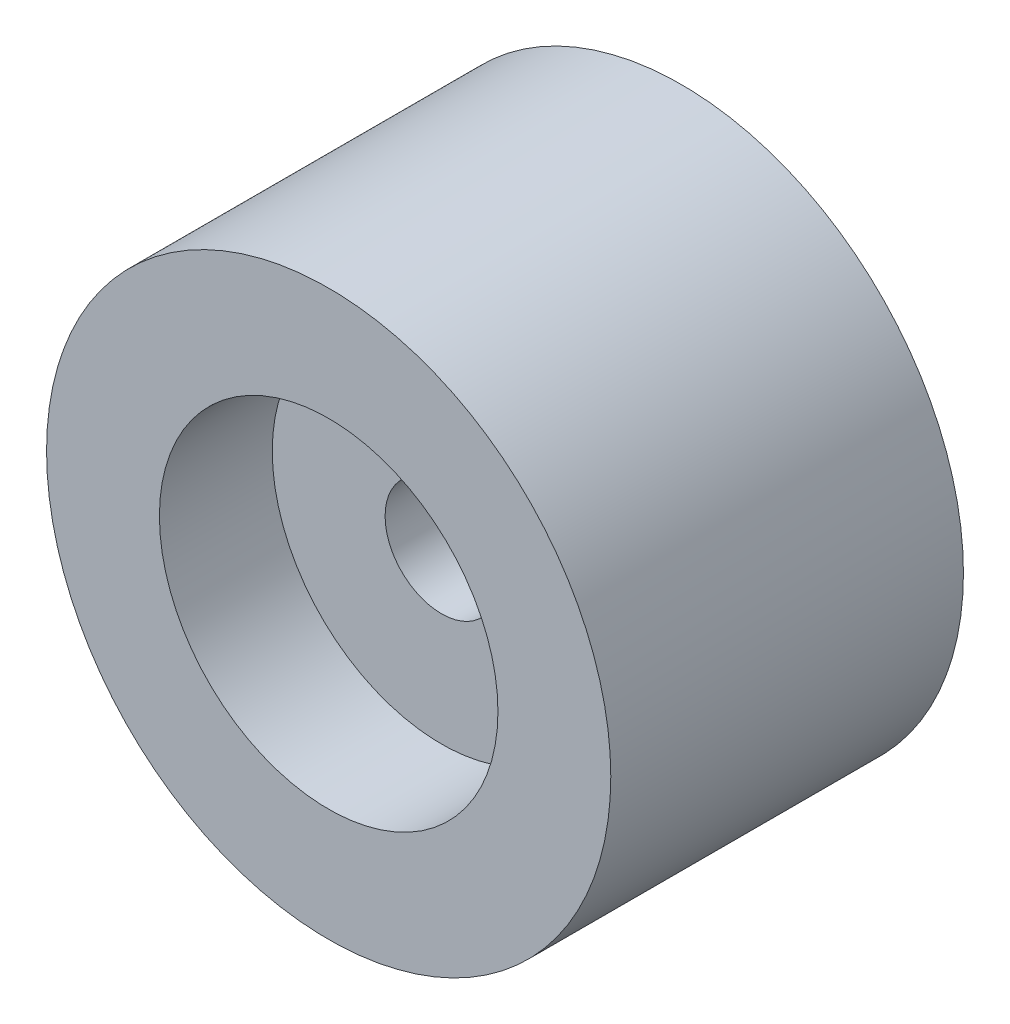
SolidWorks part; units mm, degrees
ref_plane "前视基准面" through (0, 0, 0) normal (0, 0, 1) x (1, 0, 0)
ref_plane "上视基准面" through (0, 0, 0) normal (0, 1, 0) x (1, 0, 0)
ref_plane "右视基准面" through (0, 0, 0) normal (1, 0, 0) x (0, 0, -1)
sketch "草图1" plane through (0, 0, 0) normal (0, 0, 1) x (1, 0, 0)
  circle A0 centre (-43.9206, 23.4) radius 20
  circle A1 centre (-43.9206, 23.4) radius 4
  dimension "D1" = 40
  dimension "D2" = 8
extrude "凸台-拉伸1" add sketch "草图1" along normal blind 25
sketch "草图2" plane through (0, 0, 25) normal (0, 0, 1) x (1, 0, 0)
  circle A0 centre (-43.9206, 23.4) radius 12
  dimension "D1" = 24
extrude "切除-拉伸1" cut sketch "草图2" against normal blind 8 contours A0
sketch "草图3" plane through (0, 0, 0) normal (0, 0, -1) x (-1, 0, 0)
  circle A0 centre (43.9206, 23.4) radius 12
extrude "切除-拉伸2" cut sketch "草图3" against normal blind 8
